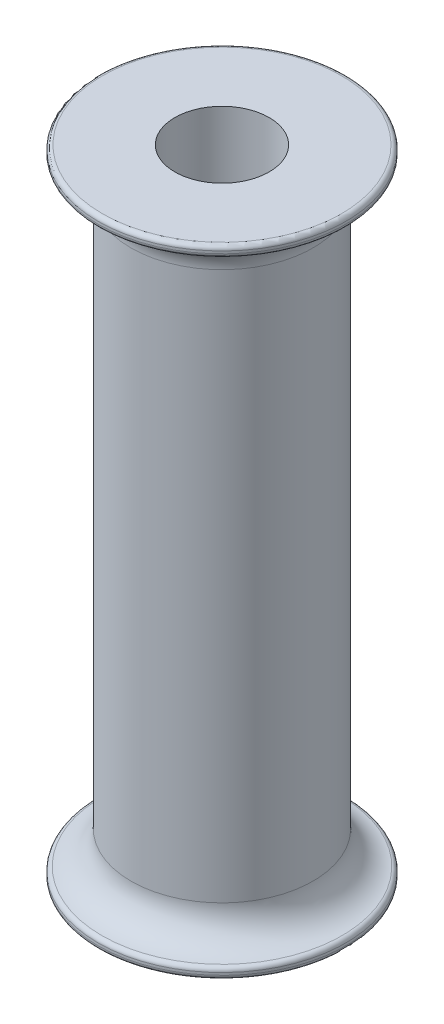
SolidWorks part; units mm, degrees
ref_plane "Front Plane" through (0, 0, 0) normal (0, 0, 1) x (1, 0, 0)
ref_plane "Top Plane" through (0, 0, 0) normal (0, 1, 0) x (1, 0, 0)
ref_plane "Right Plane" through (0, 0, 0) normal (1, 0, 0) x (0, 0, -1)
sketch "Sketch4" plane through (0, 0, 0) normal (1, 0, 0) x (0, 0, -1)
  line L0 (0, 0) -> (2, 0) construction
  line L1 (2, -12.5) -> (2, 12.5)
  line L2 (2, 12.5) -> (3.5, 12.5) construction
  line L3 (2, -12.5) -> (3.5, -12.5) construction
  line L4 (0, -14) -> (0, 14)
  line L7 (0, 0) -> (-2.15, 0) construction
  line L8 (-2.15, 0) -> (-2.15, 4.5664) construction
  line L11 (3.5, 14) -> (3.5, 14.5)
  line L12 (3.5, 14.5) -> (0, 14.5)
  line L13 (0, 14) -> (0, 14.5)
  line L15 (3.5, -14) -> (3.5, -14.5)
  line L16 (3.5, -14.5) -> (0, -14.5)
  line L17 (0, -14) -> (0, -14.5)
  arc A0 (2, 12.5) -> (3.5, 14) centre (3.5, 12.5) cw
  arc A1 (2, -12.5) -> (3.5, -14) centre (3.5, -12.5) ccw
  point P6 (2, 0)
  point P12 (0, 0)
  point P14 (0, 0)
  dimension "D1" = 2
  dimension "D2" = 25
  dimension "D3" = 1.5
  dimension "D4" = 2.15
  dimension "D5" = 0.5
  dimension "D6" = 0.5
revolve "Revolve2" add sketch "Sketch4" angle 360 about L8
fillet "Fillet2" radius 0.2 4 edges at (0, -14.5, -3.5) (0, -14, -3.5) (0, 14, -3.5) (0, 14.5, -3.5)
